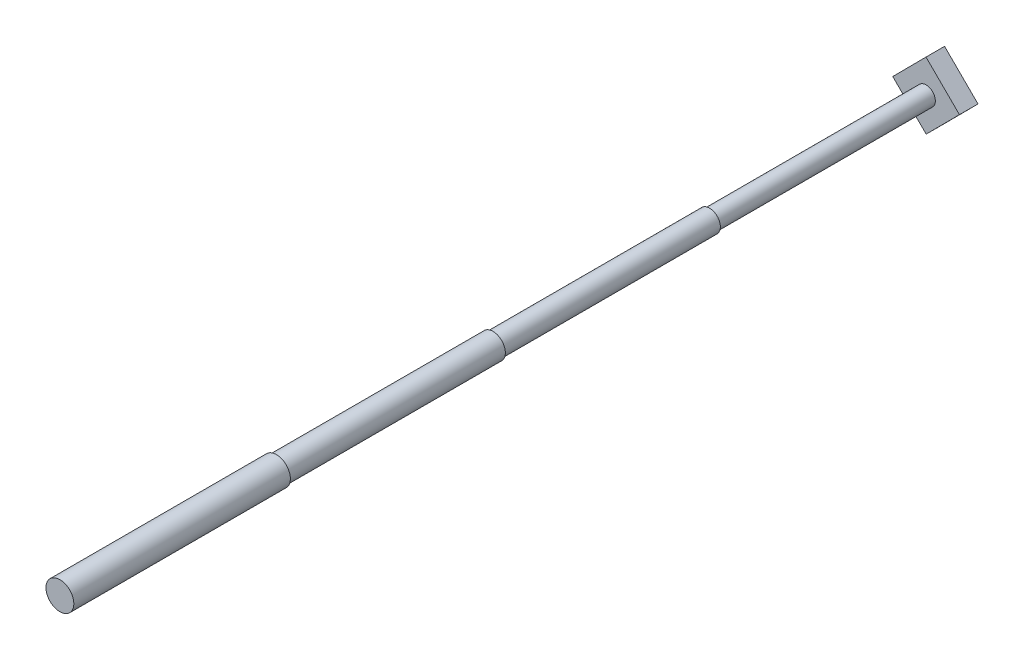
SolidWorks part; units mm, degrees
ref_plane "Plan de face" through (0, 0, 0) normal (0, 0, 1) x (1, 0, 0)
ref_plane "Plan de dessus" through (0, 0, 0) normal (0, 1, 0) x (1, 0, 0)
ref_plane "Plan de droite" through (0, 0, 0) normal (1, 0, 0) x (0, 0, -1)
sketch "Esquisse1" plane through (0, 0, 0) normal (0, 0, 1) x (1, 0, 0)
  circle A0 centre (-5.056, 0.2083) radius 45
extrude "Boss.-Extru.1" add sketch "Esquisse1" along normal blind 700
sketch "Esquisse2" plane through (0, 0, 0) normal (0, 0, -1) x (-1, 0, 0)
  circle A2 centre (5.056, 0.2083) radius 40
  circle A3 centre (5.056, 0.2083) radius 40
  dimension "D1" = 5
extrude "Boss.-Extru.4" add sketch "Esquisse2" along normal blind 700
sketch "Esquisse3" plane through (0, 0, -700) normal (0, 0, -1) x (-1, 0, 0)
  circle A2 centre (5.056, 0.2083) radius 35
  circle A3 centre (5.056, 0.2083) radius 35
  dimension "D1" = 5
extrude "Boss.-Extru.5" add sketch "Esquisse3" along normal blind 700
sketch "Esquisse4" plane through (0, 0, -1400) normal (0, 0, -1) x (-1, 0, 0)
  circle A2 centre (5.056, 0.2083) radius 30
  circle A3 centre (5.056, 0.2083) radius 30
  dimension "D1" = 5
extrude "Boss.-Extru.6" add sketch "Esquisse4" along normal blind 700
sketch "Esquisse5" plane through (0, 0, -2100) normal (0, 0, -1) x (-1, 0, 0)
  line L4 (4.7859, -107.573) -> (112.8365, -0.2701)
  line L5 (112.8365, -0.2701) -> (5.3056, 108.0102)
  line L6 (-102.7451, 0.7073) -> (5.3056, 108.0102)
  line L7 (4.7859, -107.573) -> (-102.7451, 0.7073)
extrude "Boss.-Extru.7" add sketch "Esquisse5" along normal blind 60
